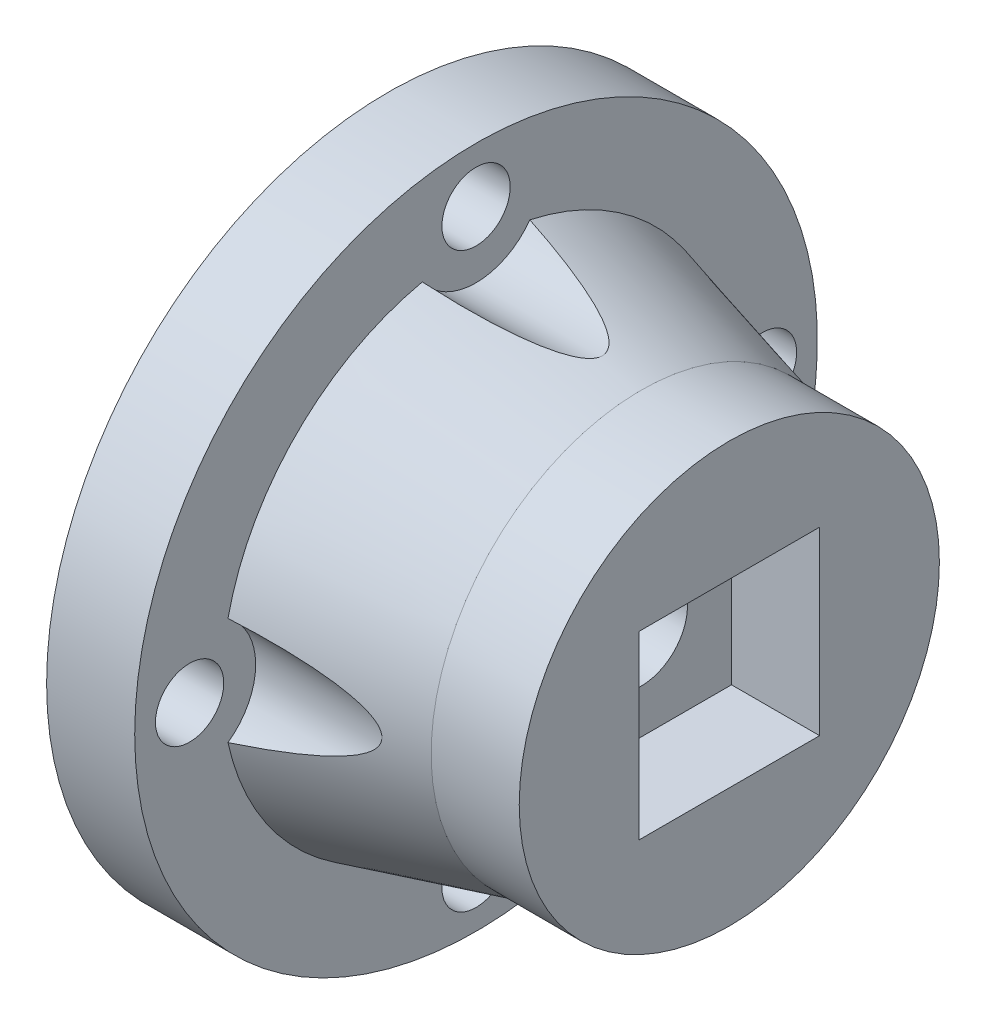
SolidWorks part; units mm, degrees
ref_plane "Plan de face" through (0, 0, 0) normal (0, 0, 1) x (1, 0, 0)
ref_plane "Plan de dessus" through (0, 0, 0) normal (0, 1, 0) x (1, 0, 0)
ref_plane "Plan de droite" through (0, 0, 0) normal (1, 0, 0) x (0, 0, -1)
sketch "Esquisse1" plane through (0, 0, 0) normal (0, 0, 1) x (1, 0, 0)
  line L0 (1.5, 15.5) -> (1.5, 10.5142)
  line L1 (11, 5) -> (-11, 5) construction
  line L2 (1.5, 10.5142) -> (11, 8)
  line L3 (11, 8) -> (11, 5)
  line L4 (11, 5) -> (7, 5)
  line L6 (7, 5) -> (7, 2.1)
  line L7 (11, 0) -> (11, 8) construction
  line L8 (0, 0) -> (15.2159, 0) construction
  line L9 (1.5, 0) -> (1.5, 15.5) construction
  line L11 (7, 2.1) -> (13, 2.1)
  line L12 (13, 2.1) -> (13, 9.5395)
  line L13 (13, 9.5395) -> (5.5, 11.5244)
  line L14 (5.5, 11.5244) -> (5.5, 15.5)
  line L15 (5.5, 15.5) -> (1.5, 15.5)
  line L16 (9.0594, 10.5824) -> (8.5477, 8.649) construction
  line L17 (11, 5.7941) -> (13, 5.7941) construction
  dimension "D1" = 4
  dimension "D2" = 4.2
  dimension "D3" = 2
  dimension "D4" = 4
revolve "Révolution1" add sketch "Esquisse1" angle 360 about L8
sketch "Esquisse2" plane through (13, 0, 0) normal (1, 0, 0) x (0, 0, -1)
  line L0 (6.1, -6.1) -> (6.1, 6.1) construction
  line L1 (-4.1, -4.1) -> (4.1, -4.1)
  line L2 (-4.1, -4.1) -> (-4.1, 4.1)
  line L3 (-4.1, 4.1) -> (4.1, 4.1)
  line L4 (4.1, -4.1) -> (4.1, 4.1)
  line L5 (-4.1, -4.1) -> (4.1, 4.1) construction
  line L6 (-4.1, 4.1) -> (4.1, -4.1) construction
  line L7 (-6.1, 6.1) -> (6.1, 6.1) construction
  line L8 (-6.1, -6.1) -> (-6.1, 6.1) construction
  line L9 (-6.1, -6.1) -> (6.1, -6.1) construction
  circle A0 centre (0, 0) radius 9.5395 construction
  circle A1 centre (0, 0) radius 9.5395
  point P0 (0, 0)
  dimension "D1" = 8.2
  dimension "D2" = 2
extrude "Boss.-Extru.1" add sketch "Esquisse2" along normal blind 4
sketch "Esquisse3" plane through (5.5, 0, 0) normal (1, 0, 0) x (0, 0, -1)
  line L0 (0, 10.5142) -> (0, 15.5) construction
  circle A0 centre (0, 13.0071) radius 1.55
  circle A3 centre (0, 0) radius 10.5142 construction
  circle A4 centre (0, 0) radius 15.5 construction
  dimension "D1" = 3.1
extrude "Enlèv. mat.-Extru.1" cut sketch "Esquisse3" against normal through all contours A0
sketch "Esquisse4" plane through (5.5, 0, 0) normal (1, 0, 0) x (0, 0, -1)
  circle A0 centre (0, 13.0071) radius 3
  dimension "D1" = 6
extrude "Enlèv. mat.-Extru.2" cut sketch "Esquisse4" along normal through all
pattern_circular "Répétition circulaire1" count 4 over 360 about axis through (0, 0, 0) along (1, 0, 0) of "Enlèv. mat.-Extru.2", "Enlèv. mat.-Extru.1"
